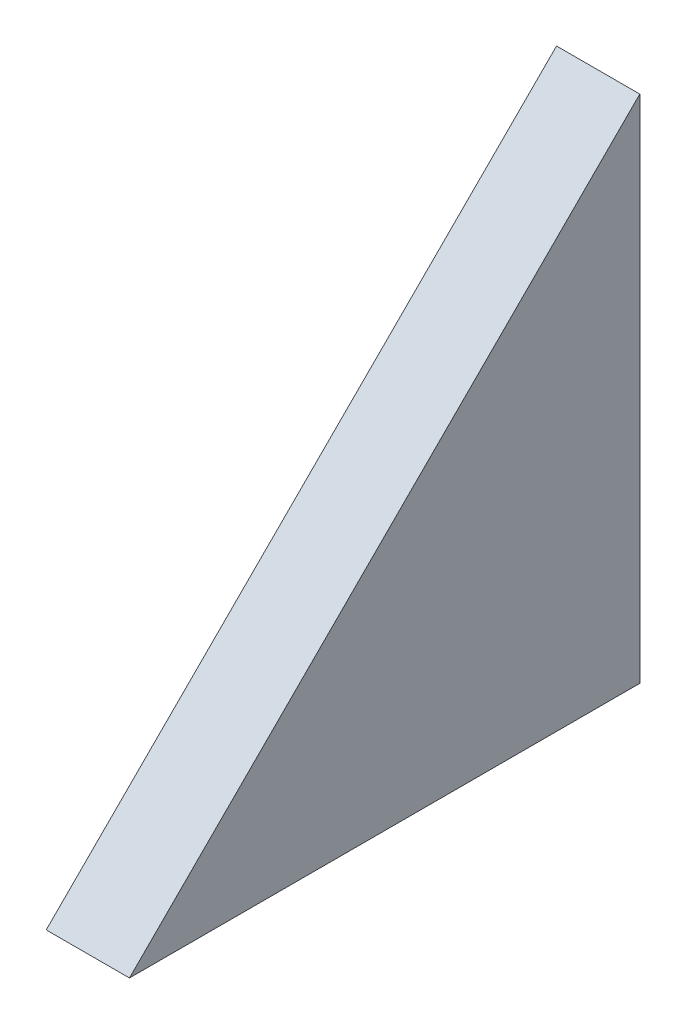
SolidWorks part; units mm, degrees
material "Plywood"
ref_plane "Front Plane" through (0, 0, 0) normal (0, 0, 1) x (1, 0, 0)
ref_plane "Top Plane" through (0, 0, 0) normal (0, 1, 0) x (1, 0, 0)
ref_plane "Right Plane" through (0, 0, 0) normal (1, 0, 0) x (0, 0, -1)
sketch "Sketch1" plane through (0, 0, 0) normal (1, 0, 0) x (0, 0, -1)
  line L0 (-39.5228, 96.9547) -> (-156.2661, -19.7886)
  line L1 (-156.2661, -19.7886) -> (-39.5228, -19.7886)
  line L2 (-39.5228, 96.9547) -> (-39.5228, -19.7886)
  dimension "D1" = 45
extrude "Boss-Extrude1" add sketch "Sketch1" along normal blind 19.05 contours L2 L1 L0
